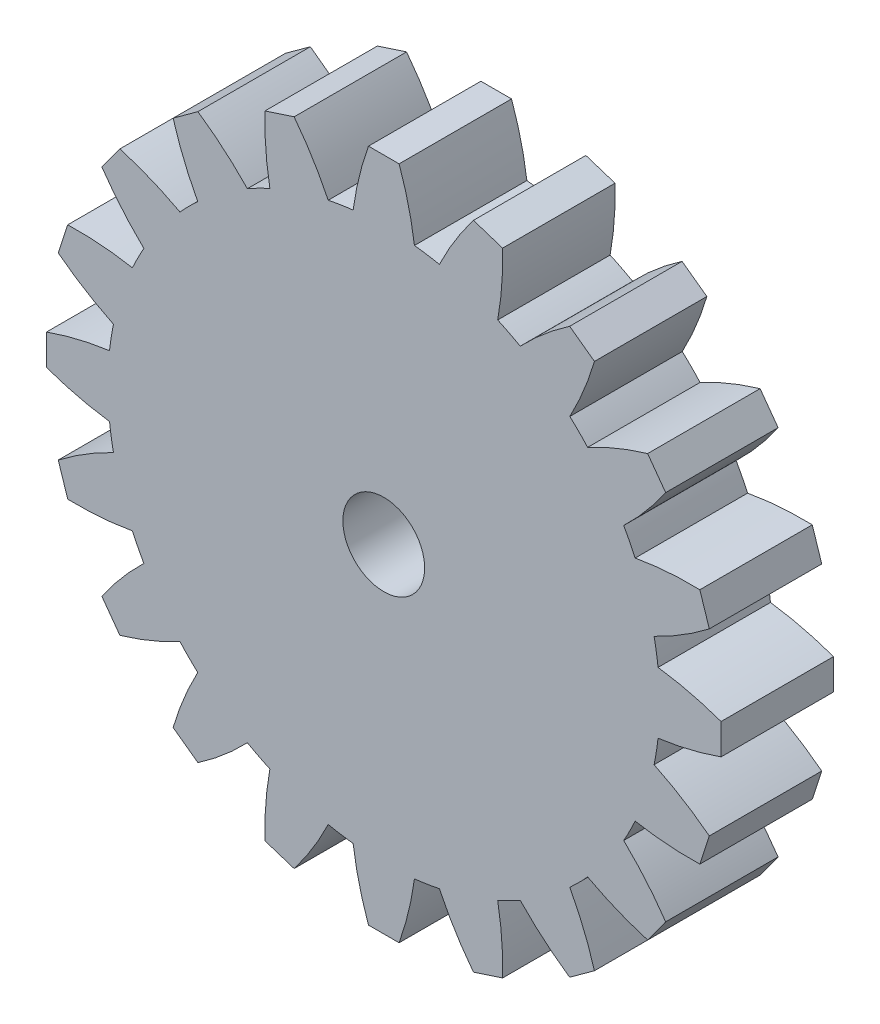
SolidWorks part; units mm, degrees
ref_plane "前视基准面" through (0, 0, 0) normal (0, 0, 1) x (1, 0, 0)
ref_plane "上视基准面" through (0, 0, 0) normal (0, 1, 0) x (1, 0, 0)
ref_plane "右视基准面" through (0, 0, 0) normal (1, 0, 0) x (0, 0, -1)
sketch "草图1" plane through (0, 0, 0) normal (0, 0, 1) x (1, 0, 0)
  circle A0 centre (0, 0) radius 13.5
extrude "凸台-拉伸1" add sketch "草图1" along normal blind 5.5
sketch "草图6" plane through (0, 0, 5.5) normal (0, 0, 1) x (1, 0, 0)
  line L0 (5.8121, 15.4607) -> (4.3855, 15.9242)
  line L1 (10.3052, 12.9079) -> (9.0917, 13.7896)
  line L2 (0.75, 16.5) -> (-0.75, 16.5)
  line L3 (13.7896, 9.0917) -> (12.9079, 10.3052)
  line L4 (15.9242, 4.3855) -> (15.4607, 5.8121)
  line L5 (16.5, -0.75) -> (16.5, 0.75)
  line L6 (15.4607, -5.8121) -> (15.9242, -4.3855)
  line L7 (12.9079, -10.3052) -> (13.7896, -9.0917)
  line L8 (9.0917, -13.7896) -> (10.3052, -12.9079)
  line L9 (4.3855, -15.9242) -> (5.8121, -15.4607)
  line L10 (-0.75, -16.5) -> (0.75, -16.5)
  line L11 (-5.8121, -15.4607) -> (-4.3855, -15.9242)
  line L12 (-10.3052, -12.9079) -> (-9.0917, -13.7896)
  line L13 (-13.7896, -9.0917) -> (-12.9079, -10.3052)
  line L14 (-15.9242, -4.3855) -> (-15.4607, -5.8121)
  line L15 (-16.5, 0.75) -> (-16.5, -0.75)
  line L16 (-15.4607, 5.8121) -> (-15.9242, 4.3855)
  line L17 (-12.9079, 10.3052) -> (-13.7896, 9.0917)
  line L18 (-9.0917, 13.7896) -> (-10.3052, 12.9079)
  line L19 (-4.3855, 15.9242) -> (-5.8121, 15.4607)
  arc A0 (1.5, 13.4164) -> (-1.5, 13.4164) centre (0, 0) ccw
  arc A1 (-0.75, 16.5) -> (-1.5, 13.4164) centre (13.6132, 11.3735) ccw
  arc A2 (0.75, 16.5) -> (1.5, 13.4164) centre (-13.6132, 11.3735) cw
  arc A3 (5.5725, 12.2962) -> (2.7193, 13.2233) centre (0, 0) ccw
  arc A4 (4.3855, 15.9242) -> (2.7193, 13.2233) centre (16.4616, 6.6101) ccw
  arc A5 (5.8121, 15.4607) -> (5.5725, 12.2962) centre (-9.4324, 15.0236) cw
  arc A6 (9.0995, 9.9724) -> (6.6724, 11.7358) centre (0, 0) ccw
  arc A7 (9.0917, 13.7896) -> (6.6724, 11.7358) centre (17.6985, 1.1997) ccw
  arc A8 (10.3052, 12.9079) -> (9.0995, 9.9724) centre (-4.3282, 17.203) cw
  arc A9 (11.7358, 6.6724) -> (9.9724, 9.0995) centre (0, 0) ccw
  arc A10 (12.9079, 10.3052) -> (9.9724, 9.0995) centre (17.203, -4.3282) ccw
  arc A11 (13.7896, 9.0917) -> (11.7358, 6.6724) centre (1.1997, 17.6985) cw
  arc A12 (13.2233, 2.7193) -> (12.2962, 5.5725) centre (0, 0) ccw
  arc A13 (15.4607, 5.8121) -> (12.2962, 5.5725) centre (15.0236, -9.4324) ccw
  arc A14 (15.9242, 4.3855) -> (13.2233, 2.7193) centre (6.6101, 16.4616) cw
  arc A15 (13.4164, -1.5) -> (13.4164, 1.5) centre (0, 0) ccw
  arc A16 (16.5, 0.75) -> (13.4164, 1.5) centre (11.3735, -13.6132) ccw
  arc A17 (16.5, -0.75) -> (13.4164, -1.5) centre (11.3735, 13.6132) cw
  arc A18 (12.2962, -5.5725) -> (13.2233, -2.7193) centre (0, 0) ccw
  arc A19 (15.9242, -4.3855) -> (13.2233, -2.7193) centre (6.6101, -16.4616) ccw
  arc A20 (15.4607, -5.8121) -> (12.2962, -5.5725) centre (15.0236, 9.4324) cw
  arc A21 (9.9724, -9.0995) -> (11.7358, -6.6724) centre (0, 0) ccw
  arc A22 (13.7896, -9.0917) -> (11.7358, -6.6724) centre (1.1997, -17.6985) ccw
  arc A23 (12.9079, -10.3052) -> (9.9724, -9.0995) centre (17.203, 4.3282) cw
  arc A24 (6.6724, -11.7358) -> (9.0995, -9.9724) centre (0, 0) ccw
  arc A25 (10.3052, -12.9079) -> (9.0995, -9.9724) centre (-4.3282, -17.203) ccw
  arc A26 (9.0917, -13.7896) -> (6.6724, -11.7358) centre (17.6985, -1.1997) cw
  arc A27 (2.7193, -13.2233) -> (5.5725, -12.2962) centre (0, 0) ccw
  arc A28 (5.8121, -15.4607) -> (5.5725, -12.2962) centre (-9.4324, -15.0236) ccw
  arc A29 (4.3855, -15.9242) -> (2.7193, -13.2233) centre (16.4616, -6.6101) cw
  arc A30 (-1.5, -13.4164) -> (1.5, -13.4164) centre (0, 0) ccw
  arc A31 (0.75, -16.5) -> (1.5, -13.4164) centre (-13.6132, -11.3735) ccw
  arc A32 (-0.75, -16.5) -> (-1.5, -13.4164) centre (13.6132, -11.3735) cw
  arc A33 (-5.5725, -12.2962) -> (-2.7193, -13.2233) centre (0, 0) ccw
  arc A34 (-4.3855, -15.9242) -> (-2.7193, -13.2233) centre (-16.4616, -6.6101) ccw
  arc A35 (-5.8121, -15.4607) -> (-5.5725, -12.2962) centre (9.4324, -15.0236) cw
  arc A36 (-9.0995, -9.9724) -> (-6.6724, -11.7358) centre (0, 0) ccw
  arc A37 (-9.0917, -13.7896) -> (-6.6724, -11.7358) centre (-17.6985, -1.1997) ccw
  arc A38 (-10.3052, -12.9079) -> (-9.0995, -9.9724) centre (4.3282, -17.203) cw
  arc A39 (-11.7358, -6.6724) -> (-9.9724, -9.0995) centre (0, 0) ccw
  arc A40 (-12.9079, -10.3052) -> (-9.9724, -9.0995) centre (-17.203, 4.3282) ccw
  arc A41 (-13.7896, -9.0917) -> (-11.7358, -6.6724) centre (-1.1997, -17.6985) cw
  arc A42 (-13.2233, -2.7193) -> (-12.2962, -5.5725) centre (0, 0) ccw
  arc A43 (-15.4607, -5.8121) -> (-12.2962, -5.5725) centre (-15.0236, 9.4324) ccw
  arc A44 (-15.9242, -4.3855) -> (-13.2233, -2.7193) centre (-6.6101, -16.4616) cw
  arc A45 (-13.4164, 1.5) -> (-13.4164, -1.5) centre (0, 0) ccw
  arc A46 (-16.5, -0.75) -> (-13.4164, -1.5) centre (-11.3735, 13.6132) ccw
  arc A47 (-16.5, 0.75) -> (-13.4164, 1.5) centre (-11.3735, -13.6132) cw
  arc A48 (-12.2962, 5.5725) -> (-13.2233, 2.7193) centre (0, 0) ccw
  arc A49 (-15.9242, 4.3855) -> (-13.2233, 2.7193) centre (-6.6101, 16.4616) ccw
  arc A50 (-15.4607, 5.8121) -> (-12.2962, 5.5725) centre (-15.0236, -9.4324) cw
  arc A51 (-9.9724, 9.0995) -> (-11.7358, 6.6724) centre (0, 0) ccw
  arc A52 (-13.7896, 9.0917) -> (-11.7358, 6.6724) centre (-1.1997, 17.6985) ccw
  arc A53 (-12.9079, 10.3052) -> (-9.9724, 9.0995) centre (-17.203, -4.3282) cw
  arc A54 (-6.6724, 11.7358) -> (-9.0995, 9.9724) centre (0, 0) ccw
  arc A55 (-10.3052, 12.9079) -> (-9.0995, 9.9724) centre (4.3282, 17.203) ccw
  arc A56 (-9.0917, 13.7896) -> (-6.6724, 11.7358) centre (-17.6985, 1.1997) cw
  arc A57 (-2.7193, 13.2233) -> (-5.5725, 12.2962) centre (0, 0) ccw
  arc A58 (-5.8121, 15.4607) -> (-5.5725, 12.2962) centre (9.4324, 15.0236) ccw
  arc A59 (-4.3855, 15.9242) -> (-2.7193, 13.2233) centre (-16.4616, 6.6101) cw
  point P125 (0, 0)
  dimension "D1" = 20
extrude "凸台-拉伸2" add sketch "草图6" against normal up to surface (5.5 mm away) up to face at (13.5, 0, 0)
sketch "草图7" plane through (0, 0, 0) normal (0, 0, -1) x (-1, 0, 0)
  circle A0 centre (0, 0) radius 2
  dimension "D1" = 4
extrude "切除-拉伸1" cut sketch "草图7" against normal through all
sketch "草图8" plane through (0, 0, 0) normal (0, 0, -1) x (-1, 0, 0)
  circle A0 centre (0, 0) radius 3
  circle A1 centre (0, 0) radius 12.5
  dimension "D1" = 25
  dimension "D2" = 6
extrude "切除-拉伸2" cut sketch "草图8" against normal blind 4
